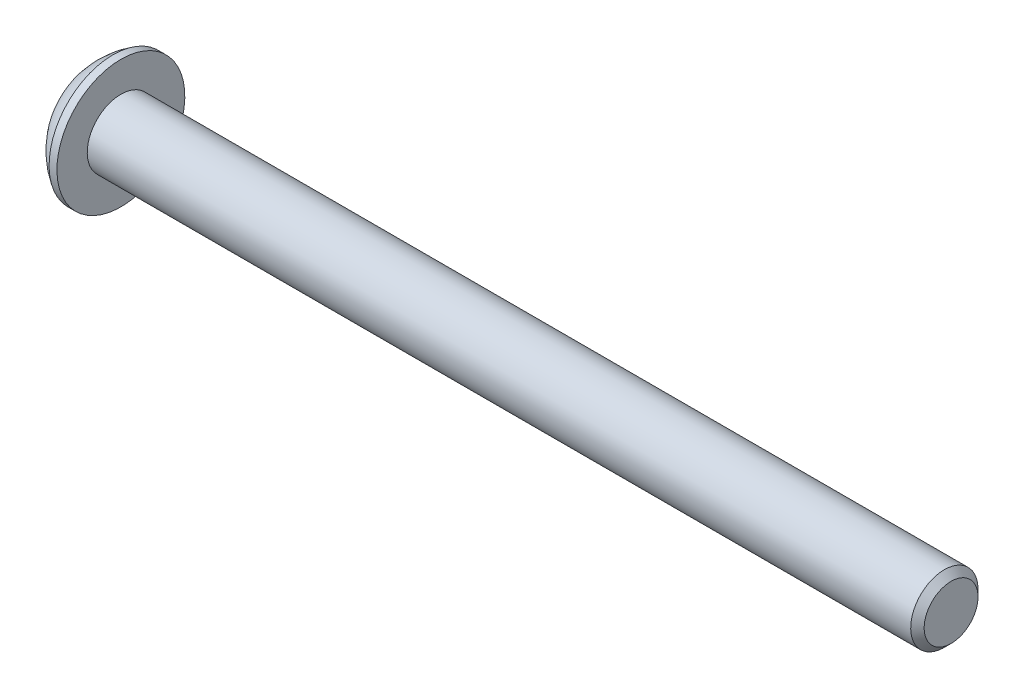
SolidWorks part; units mm, degrees
ref_plane "Plan de face" through (0, 0, 0) normal (0, 0, 1) x (1, 0, 0)
ref_plane "Plan de dessus" through (0, 0, 0) normal (0, 1, 0) x (1, 0, 0)
ref_plane "Plan de droite" through (0, 0, 0) normal (1, 0, 0) x (0, 0, -1)
sketch "Esquisse2" plane through (0, 0, 0) normal (0, 0, 1) x (1, 0, 0)
  line L0 (0, 0) -> (0, 1.425)
  line L1 (1.3, 2.85) -> (1.65, 2.85)
  line L2 (1.65, 2.85) -> (1.65, 1.5)
  line L3 (1.65, 1.5) -> (38.35, 1.5)
  line L4 (38.65, 1.2) -> (38.65, 0)
  line L5 (38.65, 0) -> (0, 0)
  line L6 (38.35, 1.5) -> (38.65, 1.2)
  arc A1 (0, 1.425) -> (1.3, 2.85) centre (3.0201, -0.0247) cw
  point P8 (38.65, 1.5)
  dimension "D5" = 3.35
  dimension "D1" = 37
  dimension "D2" = 1.5
  dimension "D3" = 2.85
  dimension "D4" = 0.35
  dimension "D6" = 1.65
  dimension "D7" = 1.425
  dimension "D8" = 0.3
  dimension "D9" = 45
revolve "Révolution1" add sketch "Esquisse2" angle 360 about L5
sketch "Esquisse3" plane through (0, 0, 0) normal (-1, 0, 0) x (0, 0, 1)
  line L1 (0, 1.1547) -> (-1, 0.5774)
  line L2 (-1, 0.5774) -> (-1, -0.5774)
  line L3 (-1, -0.5774) -> (0, -1.1547)
  line L4 (0, -1.1547) -> (1, -0.5774)
  line L5 (1, -0.5774) -> (1, 0.5774)
  line L6 (1, 0.5774) -> (0, 1.1547)
  circle A0 centre (0, 0) radius 1 construction
  dimension "D1" = 2
extrude "Enlèv. mat.-Extru.1" cut sketch "Esquisse3" against normal blind 1
